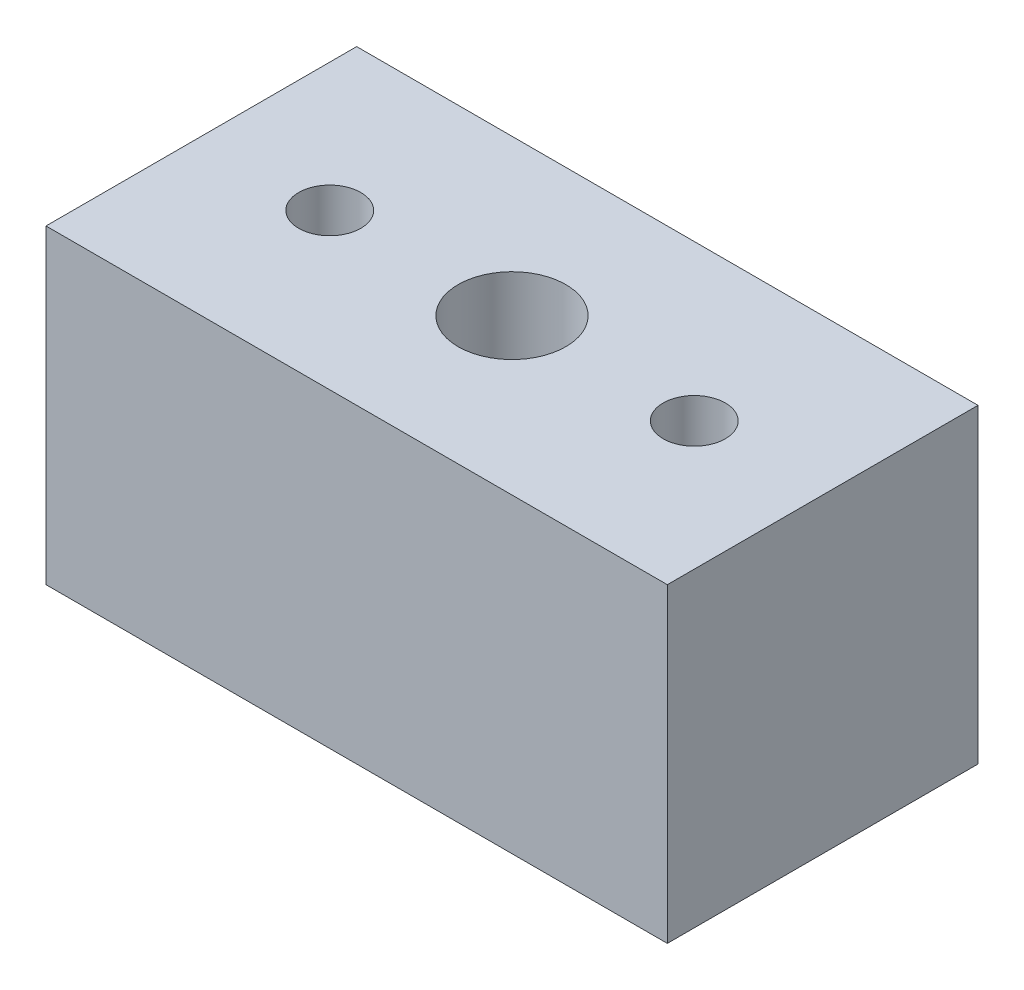
SolidWorks part; units mm, degrees
ref_plane "Front Plane" through (0, 0, 0) normal (0, 0, 1) x (1, 0, 0)
ref_plane "Top Plane" through (0, 0, 0) normal (0, 1, 0) x (1, 0, 0)
ref_plane "Right Plane" through (0, 0, 0) normal (1, 0, 0) x (0, 0, -1)
sketch "Sketch1" plane through (0, 0, 0) normal (0, 1, 0) x (1, 0, 0)
  line L1 (-15, -7.5) -> (15, -7.5)
  line L2 (-15, -7.5) -> (-15, 7.5)
  line L3 (-15, 7.5) -> (15, 7.5)
  line L4 (15, -7.5) -> (15, 7.5)
  line L5 (-15, -7.5) -> (15, 7.5) construction
  line L6 (-15, 7.5) -> (15, -7.5) construction
  point P0 (0, 0)
  dimension "D1" = 15
  dimension "D2" = 30
extrude "Boss-Extrude1" add sketch "Sketch1" along normal blind 15
sketch "Sketch2" plane through (0, 15, 0) normal (0, 1, 0) x (1, 0, 0)
  line L1 (-15, 7.5) -> (-15, -7.5) construction
  line L2 (15, -7.5) -> (15, 7.5) construction
  circle A0 centre (0, 0) radius 2.6
  circle A1 centre (-8.8, 0) radius 1.5
  circle A2 centre (8.8, 0) radius 1.5
  dimension "D1" = 5.2
  dimension "D2" = 3
  dimension "D3" = 3
  dimension "D4" = 6.2
  dimension "D5" = 6.2
extrude "Cut-Extrude1" cut sketch "Sketch2" against normal through all
